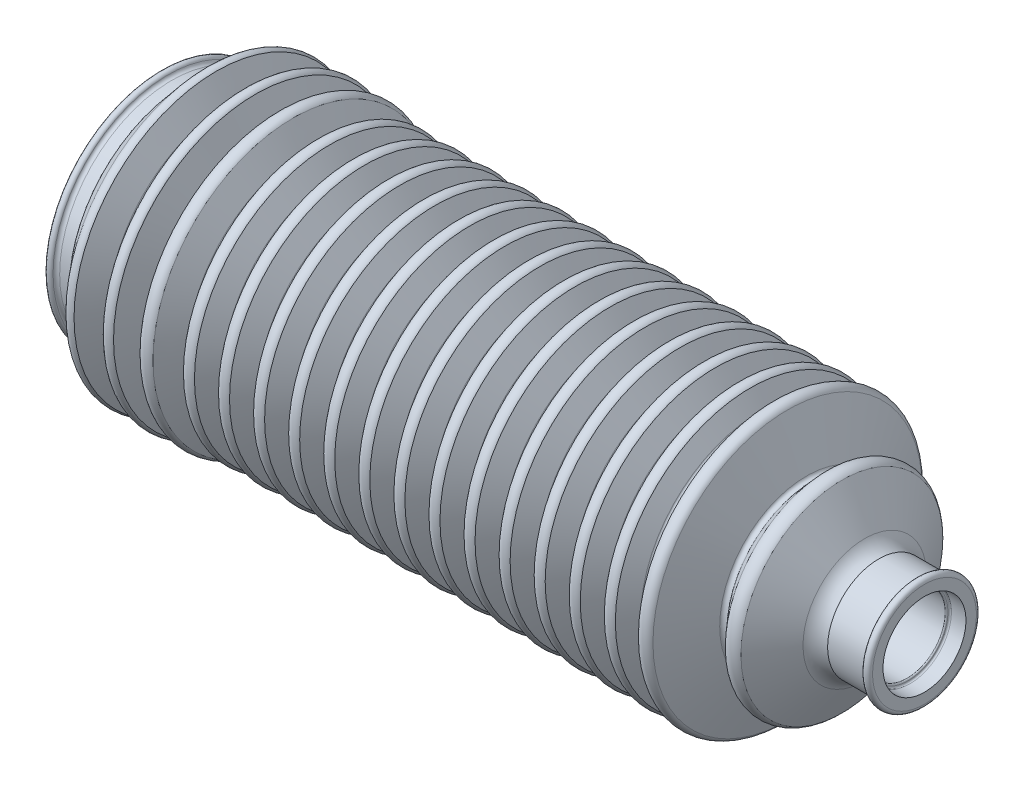
SolidWorks part; units mm, degrees
material "HYPALON"
ref_plane "Ön Düzlem" through (0, 0, 0) normal (0, 0, 1) x (1, 0, 0)
ref_plane "Üst Düzlem" through (0, 0, 0) normal (0, 1, 0) x (1, 0, 0)
ref_plane "Sağ Düzlem" through (0, 0, 0) normal (1, 0, 0) x (0, 0, -1)
sketch "Çizim1" plane through (0, 0, 0) normal (0, 0, 1) x (1, 0, 0)
  line L0 (0, 22.2692) -> (0, 0) construction
  line L1 (2.442, 25.6827) -> (5.3598, 25.6827)
  line L2 (159.0496, 8.7179) -> (170.7566, 8.7179)
  line L3 (171.4123, 9.4955) -> (174.7454, 9.4955)
  line L4 (174.7454, 11.8852) -> (174.7454, 9.4955)
  line L5 (172.7704, 11.6806) -> (164.2527, 11.6806)
  line L6 (6.6111, 21.6378) -> (0.7549, 21.6378)
  line L7 (0, 25.9338) -> (0, 22.2692)
  line L8 (0, 0) -> (172.0203, 0) construction
  line L9 (33.3502, 24.4711) -> (134.5947, 24.4711) construction
  line L10 (38.5774, 30.9585) -> (40.9478, 26.8504)
  line L11 (41.7413, 26.792) -> (43.888, 30.7082)
  line L12 (46.6071, 30.9585) -> (48.9775, 26.8504)
  line L13 (37.8696, 29.1831) -> (39.9116, 25.1153)
  line L14 (42.8114, 25.1935) -> (44.9133, 29.1397)
  line L15 (49.771, 26.792) -> (51.9177, 30.7082)
  line L16 (45.8993, 29.1831) -> (47.9413, 25.1153)
  line L17 (50.8411, 25.1935) -> (52.943, 29.1397)
  line L18 (54.6368, 30.9585) -> (57.0072, 26.8504)
  line L19 (57.8007, 26.792) -> (59.9474, 30.7082)
  line L20 (53.929, 29.1831) -> (55.971, 25.1153)
  line L21 (58.8708, 25.1935) -> (60.9727, 29.1397)
  line L22 (62.6665, 30.9585) -> (65.0369, 26.8504)
  line L23 (65.8304, 26.792) -> (67.9771, 30.7082)
  line L24 (61.9587, 29.1831) -> (64.0007, 25.1153)
  line L25 (66.9005, 25.1935) -> (69.0024, 29.1397)
  line L26 (70.6962, 30.9585) -> (73.0666, 26.8504)
  line L27 (73.8601, 26.792) -> (76.0068, 30.7082)
  line L28 (69.9884, 29.1831) -> (72.0304, 25.1153)
  line L29 (74.9302, 25.1935) -> (77.0321, 29.1397)
  line L30 (78.7259, 30.9585) -> (81.0963, 26.8504)
  line L31 (81.8898, 26.792) -> (84.0365, 30.7082)
  line L32 (78.0181, 29.1831) -> (80.0601, 25.1153)
  line L33 (82.9599, 25.1935) -> (85.0618, 29.1397)
  line L34 (86.7556, 30.9585) -> (89.126, 26.8504)
  line L35 (89.9195, 26.792) -> (92.0662, 30.7082)
  line L36 (86.0478, 29.1831) -> (88.0898, 25.1153)
  line L37 (90.9896, 25.1935) -> (93.0915, 29.1397)
  line L38 (94.7853, 30.9585) -> (97.1557, 26.8504)
  line L39 (97.9492, 26.792) -> (100.0959, 30.7082)
  line L40 (94.0775, 29.1831) -> (96.1194, 25.1153)
  line L41 (99.0193, 25.1935) -> (101.1212, 29.1397)
  line L42 (102.815, 30.9585) -> (105.1854, 26.8504)
  line L43 (5.9969, 26.9473) -> (10.7103, 32.5227)
  line L44 (12.6249, 32.571) -> (15.3982, 27.4296)
  line L45 (16.7324, 27.3848) -> (19.2061, 32.4411)
  line L46 (21.5594, 32.4651) -> (23.8545, 27.0561)
  line L47 (24.8114, 26.9564) -> (27.3089, 32.1442)
  line L48 (30.1893, 32.0681) -> (32.9181, 26.8504)
  line L49 (33.7116, 26.792) -> (35.8583, 30.7082)
  line L50 (105.9789, 26.792) -> (108.1256, 30.7082)
  line L51 (7.4522, 23.8888) -> (11.0075, 30.7026)
  line L52 (11.7352, 30.7127) -> (14.9184, 25.0598)
  line L53 (17.8403, 25.8116) -> (19.7985, 30.6604)
  line L54 (20.7159, 30.6784) -> (23.0111, 25.2194)
  line L55 (26.0219, 25.2879) -> (28.3832, 30.5369)
  line L56 (29.2326, 30.4418) -> (31.8819, 25.1153)
  line L57 (34.7817, 25.1935) -> (36.8836, 29.1397)
  line L58 (102.1072, 29.1831) -> (104.1491, 25.1153)
  line L59 (134.9338, 30.9585) -> (137.0031, 27.2312)
  line L60 (138.095, 27.1587) -> (140.4475, 31.1982)
  line L61 (143.388, 30.7993) -> (147.7567, 19.8913)
  line L62 (149.2933, 19.7465) -> (152.5709, 23.4228)
  line L63 (155.8386, 23.1093) -> (161.0568, 14.1225)
  line L64 (107.049, 25.1935) -> (109.1509, 29.1397)
  line L65 (172.7704, 11.6806) -> (173.1753, 12.5223)
  line L66 (110.8447, 30.9585) -> (113.2151, 26.8504)
  line L67 (134.226, 29.1831) -> (136.0451, 25.2514)
  line L68 (139.4586, 25.5337) -> (141.1304, 28.8634)
  line L69 (142.0529, 28.8536) -> (146.9116, 17.7562)
  line L70 (150.8373, 17.9827) -> (153.2052, 21.29)
  line L71 (154.5718, 20.9661) -> (158.3881, 11.112)
  line L72 (114.0086, 26.792) -> (116.1553, 30.7082)
  line L73 (110.1369, 29.1831) -> (112.1788, 25.1153)
  line L74 (37.2786, 31.5) -> (102.8319, 31.5) construction
  line L75 (115.0787, 25.1935) -> (117.1806, 29.1397)
  line L76 (118.8744, 30.9585) -> (121.2448, 26.8504)
  line L77 (122.0383, 26.792) -> (124.185, 30.7082)
  line L78 (118.1666, 29.1831) -> (120.2085, 25.1153)
  line L79 (123.1083, 25.1935) -> (125.2103, 29.1397)
  line L80 (126.9041, 30.9585) -> (129.2745, 26.8504)
  line L81 (130.068, 26.792) -> (132.2147, 30.7082)
  line L82 (126.1963, 29.1831) -> (128.2382, 25.1153)
  line L83 (131.138, 25.1935) -> (133.24, 29.1397)
  arc A0 (1.5411, 26.293) -> (2.442, 25.6827) centre (2.3441, 26.5083) ccw
  arc A1 (41.7413, 26.792) -> (40.9478, 26.8504) centre (41.3581, 27.0048) cw
  arc A2 (43.888, 30.7082) -> (46.6071, 30.9585) centre (45.3462, 29.7625) cw
  arc A3 (42.8114, 25.1935) -> (39.9116, 25.1153) centre (41.3292, 26.3509) cw
  arc A4 (44.9133, 29.1397) -> (45.8993, 29.1831) centre (45.4153, 28.9566) cw
  arc A5 (49.771, 26.792) -> (48.9775, 26.8504) centre (49.3878, 27.0048) cw
  arc A6 (51.9177, 30.7082) -> (54.6368, 30.9585) centre (53.3759, 29.7625) cw
  arc A7 (50.8411, 25.1935) -> (47.9413, 25.1153) centre (49.3589, 26.3509) cw
  arc A8 (52.943, 29.1397) -> (53.929, 29.1831) centre (53.445, 28.9566) cw
  arc A9 (57.8007, 26.792) -> (57.0072, 26.8504) centre (57.4175, 27.0048) cw
  arc A10 (59.9474, 30.7082) -> (62.6665, 30.9585) centre (61.4056, 29.7625) cw
  arc A11 (58.8708, 25.1935) -> (55.971, 25.1153) centre (57.3886, 26.3509) cw
  arc A12 (60.9727, 29.1397) -> (61.9587, 29.1831) centre (61.4747, 28.9566) cw
  arc A13 (65.8304, 26.792) -> (65.0369, 26.8504) centre (65.4472, 27.0048) cw
  arc A14 (67.9771, 30.7082) -> (70.6962, 30.9585) centre (69.4353, 29.7625) cw
  arc A15 (66.9005, 25.1935) -> (64.0007, 25.1153) centre (65.4183, 26.3509) cw
  arc A16 (69.0024, 29.1397) -> (69.9884, 29.1831) centre (69.5044, 28.9566) cw
  arc A17 (73.8601, 26.792) -> (73.0666, 26.8504) centre (73.4769, 27.0048) cw
  arc A18 (76.0068, 30.7082) -> (78.7259, 30.9585) centre (77.4649, 29.7625) cw
  arc A19 (74.9302, 25.1935) -> (72.0304, 25.1153) centre (73.448, 26.3509) cw
  arc A20 (77.0321, 29.1397) -> (78.0181, 29.1831) centre (77.5341, 28.9566) cw
  arc A21 (81.8898, 26.792) -> (81.0963, 26.8504) centre (81.5066, 27.0048) cw
  arc A22 (84.0365, 30.7082) -> (86.7556, 30.9585) centre (85.4946, 29.7625) cw
  arc A23 (82.9599, 25.1935) -> (80.0601, 25.1153) centre (81.4777, 26.3509) cw
  arc A24 (85.0618, 29.1397) -> (86.0478, 29.1831) centre (85.5638, 28.9566) cw
  arc A25 (89.9195, 26.792) -> (89.126, 26.8504) centre (89.5363, 27.0048) cw
  arc A26 (92.0662, 30.7082) -> (94.7853, 30.9585) centre (93.5243, 29.7625) cw
  arc A27 (90.9896, 25.1935) -> (88.0898, 25.1153) centre (89.5074, 26.3509) cw
  arc A28 (93.0915, 29.1397) -> (94.0775, 29.1831) centre (93.5935, 28.9566) cw
  arc A29 (97.9492, 26.792) -> (97.1557, 26.8504) centre (97.566, 27.0048) cw
  arc A30 (100.0959, 30.7082) -> (102.815, 30.9585) centre (101.554, 29.7625) cw
  arc A31 (99.0193, 25.1935) -> (96.1194, 25.1153) centre (97.5371, 26.3509) cw
  arc A32 (101.1212, 29.1397) -> (102.1072, 29.1831) centre (101.6232, 28.9566) cw
  arc A33 (105.9789, 26.792) -> (105.1854, 26.8504) centre (105.5957, 27.0048) cw
  arc A34 (108.1256, 30.7082) -> (110.8447, 30.9585) centre (109.5837, 29.7625) cw
  arc A35 (107.049, 25.1935) -> (104.1491, 25.1153) centre (105.5668, 26.3509) cw
  arc A36 (109.1509, 29.1397) -> (110.1369, 29.1831) centre (109.6529, 28.9566) cw
  arc A37 (114.0086, 26.792) -> (113.2151, 26.8504) centre (113.6254, 27.0048) cw
  arc A38 (116.1553, 30.7082) -> (118.8744, 30.9585) centre (117.6134, 29.7625) cw
  arc A39 (115.0787, 25.1935) -> (112.1788, 25.1153) centre (113.5965, 26.3509) cw
  arc A40 (117.1806, 29.1397) -> (118.1666, 29.1831) centre (117.6826, 28.9566) cw
  arc A41 (0.7549, 21.6378) -> (0, 22.2692) centre (0.7128, 22.3544) cw
  arc A42 (7.1592, 22.851) -> (6.6111, 21.6378) centre (6.2461, 22.5331) cw
  arc A43 (7.1592, 22.851) -> (7.4522, 23.8888) centre (8.9729, 22.8992) cw
  arc A44 (0, 25.9338) -> (1.5411, 26.293) centre (0.7899, 26.0304) cw
  arc A45 (5.6969, 26.3267) -> (5.3598, 25.6827) centre (4.9682, 26.2979) cw
  arc A46 (5.6969, 26.3267) -> (5.9969, 26.9473) centre (6.4125, 26.3636) cw
  arc A47 (10.7103, 32.5227) -> (12.6249, 32.571) centre (11.6929, 31.543) cw
  arc A48 (16.7324, 27.3848) -> (15.3982, 27.4296) centre (16.0734, 27.648) cw
  arc A49 (19.2061, 32.4411) -> (21.5594, 32.4651) centre (20.3914, 31.6013) cw
  arc A50 (24.8114, 26.9564) -> (23.8545, 27.0561) centre (24.3437, 27.1088) cw
  arc A51 (27.3089, 32.1442) -> (30.1893, 32.0681) centre (28.7163, 30.8669) cw
  arc A52 (33.7116, 26.792) -> (32.9181, 26.8504) centre (33.3284, 27.0048) cw
  arc A53 (35.8583, 30.7082) -> (38.5774, 30.9585) centre (37.3165, 29.7625) cw
  arc A54 (11.0075, 30.7026) -> (11.7352, 30.7127) centre (11.3732, 30.5719) cw
  arc A55 (17.8403, 25.8116) -> (14.9184, 25.0598) centre (16.1688, 26.2542) cw
  arc A56 (19.7985, 30.6604) -> (20.7159, 30.6784) centre (20.261, 30.4785) cw
  arc A57 (26.0219, 25.2879) -> (23.0111, 25.2194) centre (24.4954, 26.1827) cw
  arc A58 (28.3832, 30.5369) -> (29.2326, 30.4418) centre (28.7924, 30.351) cw
  arc A59 (34.7817, 25.1935) -> (31.8819, 25.1153) centre (33.2995, 26.3509) cw
  arc A60 (36.8836, 29.1397) -> (37.8696, 29.1831) centre (37.3856, 28.9566) cw
  arc A61 (138.095, 27.1587) -> (137.0031, 27.2312) centre (137.5603, 27.3644) cw
  arc A62 (140.4475, 31.1982) -> (143.388, 30.7993) centre (141.7727, 29.9298) cw
  arc A63 (149.2933, 19.7465) -> (147.7567, 19.8913) centre (148.5581, 20.1705) cw
  arc A64 (152.5709, 23.4228) -> (155.8386, 23.1093) centre (154.0331, 21.4764) cw
  arc A65 (164.2527, 11.6806) -> (161.0568, 14.1225) centre (165.5742, 16.7226) cw
  arc A66 (173.1753, 12.5223) -> (174.7454, 11.8852) centre (173.8385, 11.9035) cw
  arc A67 (139.4586, 25.5337) -> (136.0451, 25.2514) centre (137.6592, 26.5124) cw
  arc A68 (141.1304, 28.8634) -> (142.0529, 28.8536) centre (141.5899, 28.6975) cw
  arc A69 (150.8373, 17.9827) -> (146.9116, 17.7562) centre (148.7804, 19.4993) cw
  arc A70 (153.2052, 21.29) -> (154.5718, 20.9661) centre (153.7973, 20.7434) cw
  arc A71 (158.3881, 11.112) -> (158.366, 9.9316) centre (157.4315, 10.5395) cw
  arc A72 (159.0496, 8.7179) -> (158.366, 9.9316) centre (159.1582, 9.5784) cw
  arc A73 (171.0312, 9.0851) -> (170.7566, 8.7179) centre (170.6991, 9.0471) cw
  arc A74 (171.0312, 9.0851) -> (171.4123, 9.4955) centre (171.4197, 9.1065) cw
  circle A75 centre (2.442, 26.1827) radius 0.5 construction
  arc A76 (122.0383, 26.792) -> (121.2448, 26.8504) centre (121.6551, 27.0048) cw
  arc A77 (124.185, 30.7082) -> (126.9041, 30.9585) centre (125.6431, 29.7625) cw
  arc A78 (123.1083, 25.1935) -> (120.2085, 25.1153) centre (121.6262, 26.3509) cw
  arc A79 (125.2103, 29.1397) -> (126.1963, 29.1831) centre (125.7123, 28.9566) cw
  arc A80 (130.068, 26.792) -> (129.2745, 26.8504) centre (129.6848, 27.0048) cw
  arc A81 (132.2147, 30.7082) -> (134.9338, 30.9585) centre (133.6728, 29.7625) cw
  arc A82 (131.138, 25.1935) -> (128.2382, 25.1153) centre (129.6559, 26.3509) cw
  arc A83 (133.24, 29.1397) -> (134.226, 29.1831) centre (133.742, 28.9566) cw
revolve "Döndür1" add sketch "Çizim1" angle 360 about L8
